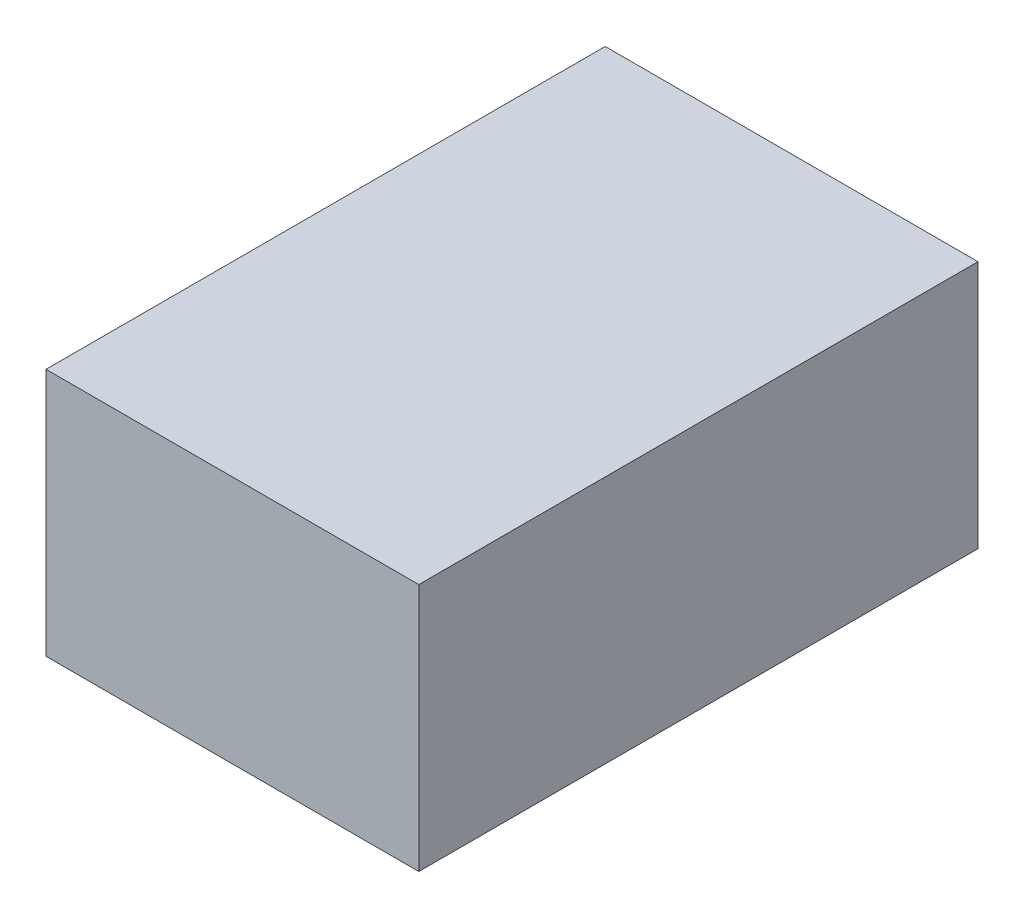
SolidWorks part; units mm, degrees
ref_plane "Front" through (0, 0, 0) normal (0, 0, 1) x (1, 0, 0)
ref_plane "Top" through (0, 0, 0) normal (0, 1, 0) x (1, 0, 0)
ref_plane "Right" through (0, 0, 0) normal (1, 0, 0) x (0, 0, -1)
sketch "Sketch1" plane through (0, 0, 0) normal (0, 1, 0) x (1, 0, 0)
  line L1 (-15, 22.5) -> (15, 22.5)
  line L2 (-15, 22.5) -> (-15, -22.5)
  line L3 (-15, -22.5) -> (15, -22.5)
  line L4 (15, 22.5) -> (15, -22.5)
  line L5 (-15, 22.5) -> (15, -22.5) construction
  line L6 (-15, -22.5) -> (15, 22.5) construction
  point P0 (0, 0)
  dimension "D1" = 30
  dimension "D2" = 45
extrude "Boss-Extrude1" add sketch "Sketch1" along normal mid plane 20
